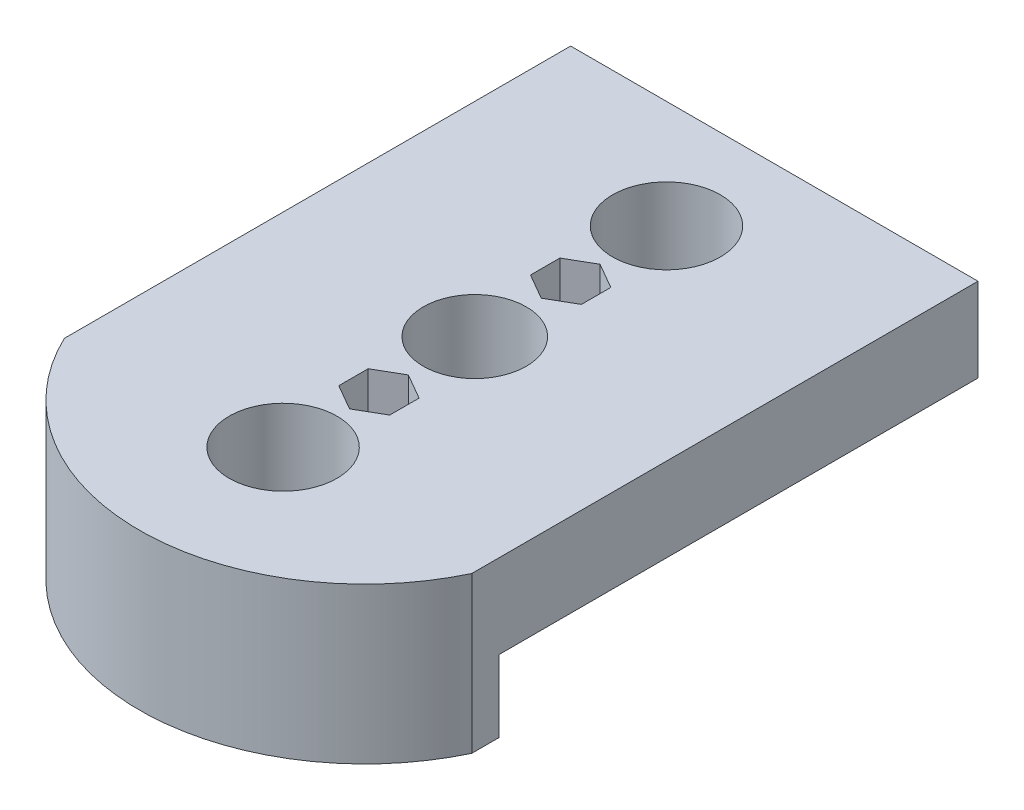
SolidWorks part; units mm, degrees
ref_plane "Front Plane" through (0, 0, 0) normal (0, 0, 1) x (1, 0, 0)
ref_plane "Top Plane" through (0, 0, 0) normal (0, 1, 0) x (1, 0, 0)
ref_plane "Right Plane" through (0, 0, 0) normal (1, 0, 0) x (0, 0, -1)
sketch "Sketch1" plane through (0, 0, 0) normal (0, 1, 0) x (1, 0, 0)
  line L1 (-17, -29) -> (17, -29)
  line L2 (-17, -29) -> (-17, 29)
  line L3 (-17, 29) -> (17, 29)
  line L4 (17, -29) -> (17, 29)
  line L5 (-17, -29) -> (17, 29) construction
  line L6 (-17, 29) -> (17, -29) construction
  point P0 (0, 0)
  dimension "D1" = 58
  dimension "D2" = 34
extrude "Boss-Extrude1" add sketch "Sketch1" along normal blind 13
sketch "Sketch3" plane through (0, 0, 0) normal (1, 0, 0) x (0, 0, -1)
  line L0 (-17, 13) -> (-12.5, 13)
  line L1 (29, 13) -> (-29, 13) construction
  line L2 (-17, 13) -> (-17, 0) construction
  line L3 (29, 0) -> (-29, 0) construction
  line L4 (-17, 0) -> (-12.5, 0)
  line L7 (-12.5, 0) -> (-12.5, 13)
  line L8 (-29, 13) -> (-29, 0) construction
  line L9 (-17, 13) -> (-17, 0)
  dimension "D1" = 4.5
  dimension "D3" = 12
revolve "Cut-Revolve1" cut sketch "Sketch3" angle 360 about L2
sketch "Sketch4" plane through (0, 0, 0) normal (0, -1, 0) x (1, 0, 0)
  line L0 (17, -29) -> (-17, -29) construction
  line L1 (3.7095, -5.425) -> (7.419, 1)
  line L2 (7.419, 1) -> (3.7095, 7.425)
  line L3 (3.7095, 7.425) -> (-3.7095, 7.425)
  line L4 (-3.7095, 7.425) -> (-7.419, 1)
  line L5 (-7.419, 1) -> (-3.7095, -5.425)
  line L6 (-3.7095, -5.425) -> (3.7095, -5.425)
  line L7 (-17, 29) -> (17, 29) construction
  circle A0 centre (0, 1) radius 6.425 construction
  point P13 (0, 29)
  dimension "D1" = 12.85
extrude "Cut-Extrude1" cut sketch "Sketch4" against normal blind 2.7
sketch "Sketch5" plane through (0, 2.7, 0) normal (0, -1, 0) x (1, 0, 0)
  line L0 (17, -29) -> (-17, -29) construction
  circle A0 centre (0, 1) radius 4.3
  point P9 (0, -29)
  dimension "D1" = 8.6
extrude "Cut-Extrude2" cut sketch "Sketch5" against normal through all
sketch "Sketch12" plane through (0, 0, 0) normal (1, 0, 0) x (0, 0, -1)
  line L0 (-1, 0) -> (15, 0)
  line L1 (29, 0) -> (-29, 0) construction
  line L2 (15, 0) -> (15, 13)
  line L3 (29, 13) -> (-29, 13) construction
  line L4 (15, 13) -> (19.5, 13)
  line L5 (19.5, 13) -> (19.5, 0)
  line L8 (19.5, 0) -> (15, 0)
  dimension "D1" = 16
  dimension "D3" = 4.5
revolve "Cut-Revolve2" cut sketch "Sketch12" angle 360 about L2
sketch "Sketch6" plane through (0, 0, -29) normal (0, 0, -1) x (-1, 0, 0)
  line L0 (-17, 6) -> (-14, 6)
  line L1 (-17, 13) -> (-17, 0) construction
  line L2 (-14, 6) -> (-14, 9)
  line L3 (-14, 9) -> (-6.6994, 9)
  line L4 (-6.6994, 9) -> (-8.8, 6)
  line L5 (-8.8, 6) -> (-8.8, 0)
  line L6 (-17, 0) -> (17, 0) construction
  line L7 (-8.8, 0) -> (-17, 0)
  line L8 (-17, 0) -> (-17, 6)
  line L9 (0, 0) -> (0, 13) construction
  line L10 (-17, 13) -> (17, 13) construction
  line L11 (8.8, 0) -> (17, 0)
  line L12 (8.8, 6) -> (8.8, 0)
  line L13 (6.6994, 9) -> (8.8, 6)
  line L14 (14, 9) -> (6.6994, 9)
  line L15 (14, 6) -> (14, 9)
  line L16 (17, 6) -> (14, 6)
  line L17 (17, 0) -> (17, 6)
  dimension "D1" = 6
  dimension "D2" = 55
  dimension "D3" = 3
  dimension "D4" = 3
  dimension "D5" = 8.2
extrude "Cut-Extrude3" cut sketch "Sketch6" against normal blind 45
sketch "Sketch7" plane through (0, 13, 0) normal (0, 1, 0) x (1, 0, 0)
  line L0 (17, -29) -> (17, 29) construction
  line L1 (-17, 29) -> (-17, -29) construction
  line L2 (17, -18.2533) -> (17, -29)
  line L3 (17, -29) -> (-17, -29)
  line L4 (-17, -29) -> (-17, -18.2533)
  arc A0 (17, -18.2533) -> (-17, -18.2533) centre (0, -10.1806) cw
  line M4 (17, -29) -> (17, 29)
  line M6 (-17, 29) -> (-17, -29)
  line M7 (-17, -29) -> (17, -29)
extrude "Cut-Extrude4" cut sketch "Sketch7" against normal through all contours A0 L3 M4 | A0 M7 M6
sketch "Sketch9" plane through (0, 0, 0) normal (0, -1, 0) x (1, 0, 0)
  line L0 (8.8, -29) -> (-8.8, -29) construction
  circle A0 centre (0, -7) radius 1.05
  circle A1 centre (0, 9) radius 1.05
  dimension "D1" = 2.1
  dimension "D2" = 2.1
  dimension "D3" = 22
  dimension "D4" = 38
extrude "Cut-Extrude6" cut sketch "Sketch9" against normal blind 13 contours A1 | A0
sketch "Sketch10" plane through (0, 13, 0) normal (0, 1, 0) x (1, 0, 0)
  line L1 (0, -6.5463) -> (-2.125, -7.7731)
  line L2 (-2.125, -7.7731) -> (-2.125, -10.2269)
  line L3 (-2.125, -10.2269) -> (0, -11.4537)
  line L4 (0, -11.4537) -> (2.125, -10.2269)
  line L5 (2.125, -10.2269) -> (2.125, -7.7731)
  line L6 (2.125, -7.7731) -> (0, -6.5463)
  line L7 (0, 9.4537) -> (-2.125, 8.2269)
  line L8 (-2.125, 8.2269) -> (-2.125, 5.7731)
  line L9 (-2.125, 5.7731) -> (0, 4.5463)
  line L10 (0, 4.5463) -> (2.125, 5.7731)
  line L11 (2.125, 5.7731) -> (2.125, 8.2269)
  line L12 (2.125, 8.2269) -> (0, 9.4537)
  circle A2 centre (0, -9) radius 2.125 construction
  circle A3 centre (0, 7) radius 2.125 construction
  dimension "D1" = 4.25
  dimension "D3" = 4.25
extrude "Cut-Extrude7" cut sketch "Sketch10" against normal blind 5.5
sketch "Sketch13" plane through (0, 13, 0) normal (0, 1, 0) x (1, 0, 0)
  line L0 (17, -18.2533) -> (17, 29) construction
  line L1 (-17, 29) -> (17, 29)
  line L2 (-17, 29) -> (-17, 24)
  line L3 (-17, 24) -> (17, 24)
  line L4 (17, 29) -> (17, 24)
  dimension "D1" = 5
extrude "Cut-Extrude8" cut sketch "Sketch13" against normal blind 15
